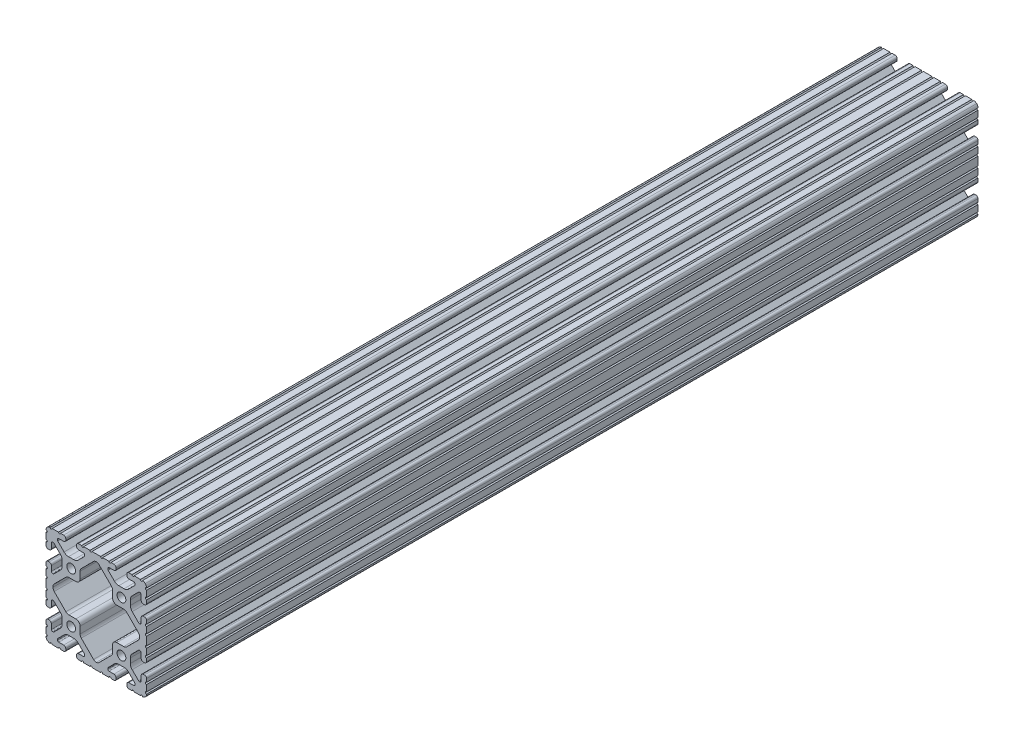
SolidWorks part; units mm, degrees
ref_plane "Front Plane" through (0, 0, 0) normal (0, 0, 1) x (1, 0, 0)
ref_plane "Top Plane" through (0, 0, 0) normal (0, 1, 0) x (1, 0, 0)
ref_plane "Right Plane" through (0, 0, 0) normal (1, 0, 0) x (0, 0, -1)
sketch "Sketch1" plane through (0, 0, 0) normal (0, 0, 1) x (1, 0, 0)
  line L0 (0, 38.1) -> (0, -38.1) construction
  line L1 (-38.1, -38.1) -> (38.1, -38.1) construction
  line L2 (-38.1, -38.1) -> (-38.1, 38.1) construction
  line L3 (-38.1, 38.1) -> (38.1, 38.1) construction
  line L4 (38.1, -38.1) -> (38.1, 38.1) construction
  line L5 (0, 38.1) -> (0, -38.1) construction
  line L6 (-38.1, 0) -> (38.1, 0) construction
  line L7 (-19.05, 19.05) -> (19.05, 19.05) construction
  line L8 (-19.05, 19.05) -> (-19.05, -19.05) construction
  line L9 (-19.05, -19.05) -> (19.05, -19.05) construction
  line L10 (19.05, 19.05) -> (19.05, -19.05) construction
  line L11 (-23.114, 38.1) -> (-23.114, -38.1) construction
  line L12 (-23.114, -38.1) -> (-14.986, 38.1) construction
  line L13 (-14.986, 38.1) -> (-14.986, -38.1) construction
  circle A0 centre (19.05, 19.05) radius 3.3274
  point P0 (0, 0)
  point P9 (0, 0)
  point P12 (-19.05, 0)
  line B0 (-11.3637, -22.8433) -> (-2.0515, -32.1555)
  line B1 (-12.2936, -15.4686) -> (-12.2936, -20.5983)
  line B2 (-20.769, -12.2936) -> (-15.4686, -12.2936)
  line B3 (-31.9021, -2.4756) -> (-23.0141, -11.3637)
  line B4 (-23.0141, 11.3637) -> (-31.9021, 2.4756)
  line B5 (-15.4686, 12.2936) -> (-20.769, 12.2936)
  line B6 (-12.2936, 20.5983) -> (-12.2936, 15.4686)
  line B7 (-2.0515, 32.1555) -> (-11.3637, 22.8433)
  line B8 (11.3637, 22.8433) -> (2.0515, 32.1555)
  line B9 (12.2936, 15.4686) -> (12.2936, 20.5983)
  line B10 (20.769, 12.2936) -> (15.4686, 12.2936)
  line B11 (31.9021, 2.4756) -> (23.0141, 11.3637)
  line B12 (23.0141, -11.3637) -> (31.9021, -2.4756)
  line B13 (15.4686, -12.2936) -> (20.769, -12.2936)
  line B14 (12.2936, -20.5983) -> (12.2936, -15.4686)
  line B15 (2.0515, -32.1555) -> (11.3637, -22.8433)
  line B16 (-4.7773, 38.1) -> (-9.6053, 38.1)
  line B17 (-11.1289, 38.1) -> (-13.4112, 38.1)
  line B18 (-14.986, 36.5252) -> (-14.986, 35.6108)
  line B19 (-13.4112, 34.036) -> (-9.652, 34.036)
  line B20 (-8.763, 33.147) -> (-8.763, 32.4935)
  line B21 (-9.0234, 31.8649) -> (-13.6907, 27.1976)
  line B22 (-17.0493, 25.8064) -> (-21.0507, 25.8064)
  line B23 (-24.4093, 27.1976) -> (-29.1002, 31.8885)
  line B24 (-29.337, 32.7207) -> (-29.337, 33.147)
  line B25 (-28.448, 34.036) -> (-24.6888, 34.036)
  line B26 (-23.114, 35.6108) -> (-23.114, 36.5252)
  line B27 (-24.6888, 38.1) -> (-27.0772, 38.1)
  line B28 (-28.6011, 38.1) -> (-33.4288, 38.1)
  line B29 (-38.1, 33.373) -> (-38.1, 28.5453)
  line B30 (-38.1, 27.0238) -> (-38.1, 24.6302)
  line B31 (-36.5252, 23.0554) -> (-35.6108, 23.0554)
  line B32 (-34.036, 24.6302) -> (-34.036, 28.448)
  line B33 (-33.147, 29.337) -> (-32.6643, 29.337)
  line B34 (-32.0357, 29.0766) -> (-27.1976, 24.2385)
  line B35 (-25.8064, 20.8799) -> (-25.8064, 17.2201)
  line B36 (-27.1976, 13.8615) -> (-31.9489, 9.1101)
  line B37 (-32.7869, 8.763) -> (-33.0603, 8.763)
  line B38 (-34.036, 9.7387) -> (-34.036, 13.4698)
  line B39 (-35.6108, 15.0446) -> (-36.5252, 15.0446)
  line B40 (-38.1, 13.4698) -> (-38.1, 11.075)
  line B41 (-38.1, 9.552) -> (-38.1, 4.7238)
  line B42 (-38.1, 3.2007) -> (-38.1, -3.2007)
  line B43 (-38.1, -4.7238) -> (-38.1, -9.552)
  line B44 (-38.1, -11.075) -> (-38.1, -13.4698)
  line B45 (-36.5252, -15.0446) -> (-35.6108, -15.0446)
  line B46 (-34.036, -13.4698) -> (-34.036, -9.7387)
  line B47 (-33.0603, -8.763) -> (-32.7869, -8.763)
  line B48 (-31.9489, -9.1101) -> (-27.1976, -13.8615)
  line B49 (-25.8064, -17.2201) -> (-25.8064, -20.8799)
  line B50 (-27.1976, -24.2385) -> (-32.0357, -29.0766)
  line B51 (-32.6643, -29.337) -> (-33.147, -29.337)
  line B52 (-34.036, -28.448) -> (-34.036, -24.6302)
  line B53 (-35.6108, -23.0554) -> (-36.5252, -23.0554)
  line B54 (-38.1, -24.6302) -> (-38.1, -27.0238)
  line B55 (-38.1, -28.5453) -> (-38.1, -33.373)
  line B56 (-33.4288, -38.1) -> (-28.6011, -38.1)
  line B57 (-27.0772, -38.1) -> (-24.6888, -38.1)
  line B58 (-23.114, -36.5252) -> (-23.114, -35.6108)
  line B59 (-24.6888, -34.036) -> (-28.448, -34.036)
  line B60 (-29.337, -33.147) -> (-29.337, -32.7207)
  line B61 (-29.1002, -31.8885) -> (-24.4093, -27.1976)
  line B62 (-21.0507, -25.8064) -> (-17.0493, -25.8064)
  line B63 (-13.6907, -27.1976) -> (-9.0234, -31.8649)
  line B64 (-8.763, -32.4935) -> (-8.763, -33.147)
  line B65 (-9.652, -34.036) -> (-13.4112, -34.036)
  line B66 (-14.986, -35.6108) -> (-14.986, -36.5252)
  line B67 (-13.4112, -38.1) -> (-11.1289, -38.1)
  line B68 (-9.6053, -38.1) -> (-4.7773, -38.1)
  line B69 (-3.2537, -38.1) -> (3.2537, -38.1)
  line B70 (4.7773, -38.1) -> (9.6053, -38.1)
  line B71 (11.1289, -38.1) -> (13.4112, -38.1)
  line B72 (14.986, -36.5252) -> (14.986, -35.6108)
  line B73 (13.4112, -34.036) -> (9.652, -34.036)
  line B74 (8.763, -33.147) -> (8.763, -32.4935)
  line B75 (9.0234, -31.8649) -> (13.6907, -27.1976)
  line B76 (17.0493, -25.8064) -> (21.0507, -25.8064)
  line B77 (24.4093, -27.1976) -> (29.1002, -31.8885)
  line B78 (29.337, -32.7207) -> (29.337, -33.147)
  line B79 (28.448, -34.036) -> (24.6888, -34.036)
  line B80 (23.114, -35.6108) -> (23.114, -36.5252)
  line B81 (24.6888, -38.1) -> (27.0772, -38.1)
  line B82 (28.6011, -38.1) -> (33.4288, -38.1)
  line B83 (38.1, -33.373) -> (38.1, -28.5453)
  line B84 (38.1, -27.0238) -> (38.1, -24.6302)
  line B85 (36.5252, -23.0554) -> (35.6108, -23.0554)
  line B86 (34.036, -24.6302) -> (34.036, -28.448)
  line B87 (33.147, -29.337) -> (32.6643, -29.337)
  line B88 (32.0357, -29.0766) -> (27.1976, -24.2385)
  line B89 (25.8064, -20.8799) -> (25.8064, -17.2201)
  line B90 (27.1976, -13.8615) -> (31.9489, -9.1101)
  line B91 (32.7869, -8.763) -> (33.0603, -8.763)
  line B92 (34.036, -9.7387) -> (34.036, -13.4698)
  line B93 (35.6108, -15.0446) -> (36.5252, -15.0446)
  line B94 (38.1, -13.4698) -> (38.1, -11.075)
  line B95 (38.1, -9.552) -> (38.1, -4.7238)
  line B96 (38.1, -3.2007) -> (38.1, 3.2007)
  line B97 (38.1, 4.7238) -> (38.1, 9.552)
  line B98 (38.1, 11.075) -> (38.1, 13.4698)
  line B99 (36.5252, 15.0446) -> (35.6108, 15.0446)
  line B100 (34.036, 13.4698) -> (34.036, 9.7387)
  line B101 (33.0603, 8.763) -> (32.7869, 8.763)
  line B102 (31.9489, 9.1101) -> (27.1976, 13.8615)
  line B103 (25.8064, 17.2201) -> (25.8064, 20.8799)
  line B104 (27.1976, 24.2385) -> (32.0357, 29.0766)
  line B105 (32.6643, 29.337) -> (33.147, 29.337)
  line B106 (34.036, 28.448) -> (34.036, 24.6302)
  line B107 (35.6108, 23.0554) -> (36.5252, 23.0554)
  line B108 (38.1, 24.6302) -> (38.1, 27.0238)
  line B109 (38.1, 28.5453) -> (38.1, 33.373)
  line B110 (33.4288, 38.1) -> (28.6011, 38.1)
  line B111 (27.0772, 38.1) -> (24.6888, 38.1)
  line B112 (23.114, 36.5252) -> (23.114, 35.6108)
  line B113 (24.6888, 34.036) -> (28.448, 34.036)
  line B114 (29.337, 33.147) -> (29.337, 32.7207)
  line B115 (29.1002, 31.8885) -> (24.4093, 27.1976)
  line B116 (21.0507, 25.8064) -> (17.0493, 25.8064)
  line B117 (13.6907, 27.1976) -> (9.0234, 31.8649)
  line B118 (8.763, 32.4935) -> (8.763, 33.147)
  line B119 (9.652, 34.036) -> (13.4112, 34.036)
  line B120 (14.986, 35.6108) -> (14.986, 36.5252)
  line B121 (13.4112, 38.1) -> (11.1289, 38.1)
  line B122 (9.6053, 38.1) -> (4.7773, 38.1)
  line B123 (3.2537, 38.1) -> (-3.2537, 38.1)
  circle B124 centre (-19.05, 19.05) radius 3.3274
  circle B125 centre (-19.05, -19.05) radius 3.3274
  circle B126 centre (19.05, -19.05) radius 3.3274
  circle B127 centre (19.05, 19.05) radius 3.3274
  arc B128 (0, -33.011) -> (2.0515, -32.1555) centre (-0.0139, -30.09) ccw
  arc B129 (-2.0515, -32.1555) -> (0, -33.011) centre (0.0139, -30.09) ccw
  arc B130 (-12.2936, -20.5983) -> (-11.3637, -22.8433) centre (-9.1186, -20.5983) ccw
  arc B131 (-12.2936, -15.4686) -> (-15.4686, -12.2936) centre (-15.4686, -15.4686) ccw
  arc B132 (-23.0141, -11.3637) -> (-20.769, -12.2936) centre (-20.769, -9.1186) ccw
  arc B133 (-32.7287, 0) -> (-31.9021, -2.4756) centre (-29.8367, -0.4102) ccw
  arc B134 (-31.9021, 2.4756) -> (-32.7287, 0) centre (-29.8367, 0.4102) ccw
  arc B135 (-20.769, 12.2936) -> (-23.0141, 11.3637) centre (-20.769, 9.1186) ccw
  arc B136 (-15.4686, 12.2936) -> (-12.2936, 15.4686) centre (-15.4686, 15.4686) ccw
  arc B137 (-11.3637, 22.8433) -> (-12.2936, 20.5983) centre (-9.1186, 20.5983) ccw
  arc B138 (0, 33.011) -> (-2.0515, 32.1555) centre (0.0139, 30.09) ccw
  arc B139 (2.0515, 32.1555) -> (0, 33.011) centre (-0.0139, 30.09) ccw
  arc B140 (12.2936, 20.5983) -> (11.3637, 22.8433) centre (9.1186, 20.5983) ccw
  arc B141 (12.2936, 15.4686) -> (15.4686, 12.2936) centre (15.4686, 15.4686) ccw
  arc B142 (23.0141, 11.3637) -> (20.769, 12.2936) centre (20.769, 9.1186) ccw
  arc B143 (32.7287, 0) -> (31.9021, 2.4756) centre (29.8367, 0.4102) ccw
  arc B144 (31.9021, -2.4756) -> (32.7287, 0) centre (29.8367, -0.4102) ccw
  arc B145 (20.769, -12.2936) -> (23.0141, -11.3637) centre (20.769, -9.1186) ccw
  arc B146 (15.4686, -12.2936) -> (12.2936, -15.4686) centre (15.4686, -15.4686) ccw
  arc B147 (11.3637, -22.8433) -> (12.2936, -20.5983) centre (9.1186, -20.5983) ccw
  arc B148 (-4.7773, 38.1) -> (-3.2537, 38.1) centre (-4.0155, 38.0824) ccw
  arc B149 (-11.1289, 38.1) -> (-9.6053, 38.1) centre (-10.3671, 38.0824) ccw
  arc B150 (-13.4112, 38.1) -> (-14.986, 36.5252) centre (-13.4112, 36.5252) ccw
  arc B151 (-14.986, 35.6108) -> (-13.4112, 34.036) centre (-13.4112, 35.6108) ccw
  arc B152 (-8.763, 33.147) -> (-9.652, 34.036) centre (-9.652, 33.147) ccw
  arc B153 (-9.0234, 31.8649) -> (-8.763, 32.4935) centre (-9.652, 32.4935) ccw
  arc B154 (-17.0493, 25.8064) -> (-13.6907, 27.1976) centre (-17.0493, 30.5562) ccw
  arc B155 (-24.4093, 27.1976) -> (-21.0507, 25.8064) centre (-21.0507, 30.5562) ccw
  arc B156 (-29.337, 32.7207) -> (-29.1002, 31.8885) centre (-28.4716, 32.5172) ccw
  arc B157 (-28.448, 34.036) -> (-29.337, 33.147) centre (-28.448, 33.147) ccw
  arc B158 (-24.6888, 34.036) -> (-23.114, 35.6108) centre (-24.6888, 35.6108) ccw
  arc B159 (-23.114, 36.5252) -> (-24.6888, 38.1) centre (-24.6888, 36.5252) ccw
  arc B160 (-28.6011, 38.1) -> (-27.0772, 38.1) centre (-27.8392, 38.0824) ccw
  arc B161 (-34.9527, 38.1) -> (-33.4288, 38.1) centre (-34.1907, 38.0824) ccw
  arc B162 (-34.9527, 38.1) -> (-37.0861, 37.1826) centre (-34.8521, 34.9266) ccw
  arc B163 (-37.0861, 37.1826) -> (-38.1, 34.8455) centre (-34.925, 34.8566) ccw
  arc B164 (-38.1, 33.373) -> (-38.1, 34.8455) centre (-37.9035, 34.1092) ccw
  arc B165 (-38.1, 27.0238) -> (-38.1, 28.5453) centre (-37.9035, 27.7845) ccw
  arc B166 (-38.1, 24.6302) -> (-36.5252, 23.0554) centre (-36.5252, 24.6302) ccw
  arc B167 (-35.6108, 23.0554) -> (-34.036, 24.6302) centre (-35.6108, 24.6302) ccw
  arc B168 (-33.147, 29.337) -> (-34.036, 28.448) centre (-33.147, 28.448) ccw
  arc B169 (-32.0357, 29.0766) -> (-32.6643, 29.337) centre (-32.6643, 28.448) ccw
  arc B170 (-25.8064, 20.8799) -> (-27.1976, 24.2385) centre (-30.5562, 20.8799) ccw
  arc B171 (-27.1976, 13.8615) -> (-25.8064, 17.2201) centre (-30.5562, 17.2201) ccw
  arc B172 (-32.7869, 8.763) -> (-31.9489, 9.1101) centre (-32.7869, 9.9481) ccw
  arc B173 (-34.036, 9.7387) -> (-33.0603, 8.763) centre (-33.0603, 9.7387) ccw
  arc B174 (-34.036, 13.4698) -> (-35.6108, 15.0446) centre (-35.6108, 13.4698) ccw
  arc B175 (-36.5252, 15.0446) -> (-38.1, 13.4698) centre (-36.5252, 13.4698) ccw
  arc B176 (-38.1, 9.552) -> (-38.1, 11.075) centre (-37.9035, 10.3135) ccw
  arc B177 (-38.1, 3.2007) -> (-38.1, 4.7238) centre (-37.9035, 3.9622) ccw
  arc B178 (-38.1, -4.7238) -> (-38.1, -3.2007) centre (-37.9035, -3.9622) ccw
  arc B179 (-38.1, -11.075) -> (-38.1, -9.552) centre (-37.9035, -10.3135) ccw
  arc B180 (-38.1, -13.4698) -> (-36.5252, -15.0446) centre (-36.5252, -13.4698) ccw
  arc B181 (-35.6108, -15.0446) -> (-34.036, -13.4698) centre (-35.6108, -13.4698) ccw
  arc B182 (-33.0603, -8.763) -> (-34.036, -9.7387) centre (-33.0603, -9.7387) ccw
  arc B183 (-31.9489, -9.1101) -> (-32.7869, -8.763) centre (-32.7869, -9.9481) ccw
  arc B184 (-25.8064, -17.2201) -> (-27.1976, -13.8615) centre (-30.5562, -17.2201) ccw
  arc B185 (-27.1976, -24.2385) -> (-25.8064, -20.8799) centre (-30.5562, -20.8799) ccw
  arc B186 (-32.6643, -29.337) -> (-32.0357, -29.0766) centre (-32.6643, -28.448) ccw
  arc B187 (-34.036, -28.448) -> (-33.147, -29.337) centre (-33.147, -28.448) ccw
  arc B188 (-34.036, -24.6302) -> (-35.6108, -23.0554) centre (-35.6108, -24.6302) ccw
  arc B189 (-36.5252, -23.0554) -> (-38.1, -24.6302) centre (-36.5252, -24.6302) ccw
  arc B190 (-38.1, -28.5453) -> (-38.1, -27.0238) centre (-37.9035, -27.7845) ccw
  arc B191 (-38.1, -34.8455) -> (-38.1, -33.373) centre (-37.9035, -34.1092) ccw
  arc B192 (-38.1, -34.8455) -> (-37.0861, -37.1826) centre (-34.925, -34.8566) ccw
  arc B193 (-37.0861, -37.1826) -> (-34.9527, -38.1) centre (-34.8521, -34.9266) ccw
  arc B194 (-33.4288, -38.1) -> (-34.9527, -38.1) centre (-34.1907, -38.0824) ccw
  arc B195 (-27.0772, -38.1) -> (-28.6011, -38.1) centre (-27.8392, -38.0824) ccw
  arc B196 (-24.6888, -38.1) -> (-23.114, -36.5252) centre (-24.6888, -36.5252) ccw
  arc B197 (-23.114, -35.6108) -> (-24.6888, -34.036) centre (-24.6888, -35.6108) ccw
  arc B198 (-29.337, -33.147) -> (-28.448, -34.036) centre (-28.448, -33.147) ccw
  arc B199 (-29.1002, -31.8885) -> (-29.337, -32.7207) centre (-28.4716, -32.5172) ccw
  arc B200 (-21.0507, -25.8064) -> (-24.4093, -27.1976) centre (-21.0507, -30.5562) ccw
  arc B201 (-13.6907, -27.1976) -> (-17.0493, -25.8064) centre (-17.0493, -30.5562) ccw
  arc B202 (-8.763, -32.4935) -> (-9.0234, -31.8649) centre (-9.652, -32.4935) ccw
  arc B203 (-9.652, -34.036) -> (-8.763, -33.147) centre (-9.652, -33.147) ccw
  arc B204 (-13.4112, -34.036) -> (-14.986, -35.6108) centre (-13.4112, -35.6108) ccw
  arc B205 (-14.986, -36.5252) -> (-13.4112, -38.1) centre (-13.4112, -36.5252) ccw
  arc B206 (-9.6053, -38.1) -> (-11.1289, -38.1) centre (-10.3671, -38.0824) ccw
  arc B207 (-3.2537, -38.1) -> (-4.7773, -38.1) centre (-4.0155, -38.0824) ccw
  arc B208 (4.7773, -38.1) -> (3.2537, -38.1) centre (4.0155, -38.0824) ccw
  arc B209 (11.1289, -38.1) -> (9.6053, -38.1) centre (10.3671, -38.0824) ccw
  arc B210 (13.4112, -38.1) -> (14.986, -36.5252) centre (13.4112, -36.5252) ccw
  arc B211 (14.986, -35.6108) -> (13.4112, -34.036) centre (13.4112, -35.6108) ccw
  arc B212 (8.763, -33.147) -> (9.652, -34.036) centre (9.652, -33.147) ccw
  arc B213 (9.0234, -31.8649) -> (8.763, -32.4935) centre (9.652, -32.4935) ccw
  arc B214 (17.0493, -25.8064) -> (13.6907, -27.1976) centre (17.0493, -30.5562) ccw
  arc B215 (24.4093, -27.1976) -> (21.0507, -25.8064) centre (21.0507, -30.5562) ccw
  arc B216 (29.337, -32.7207) -> (29.1002, -31.8885) centre (28.4716, -32.5172) ccw
  arc B217 (28.448, -34.036) -> (29.337, -33.147) centre (28.448, -33.147) ccw
  arc B218 (24.6888, -34.036) -> (23.114, -35.6108) centre (24.6888, -35.6108) ccw
  arc B219 (23.114, -36.5252) -> (24.6888, -38.1) centre (24.6888, -36.5252) ccw
  arc B220 (28.6011, -38.1) -> (27.0772, -38.1) centre (27.8392, -38.0824) ccw
  arc B221 (34.9527, -38.1) -> (33.4288, -38.1) centre (34.1907, -38.0824) ccw
  arc B222 (34.9527, -38.1) -> (37.0861, -37.1826) centre (34.8521, -34.9266) ccw
  arc B223 (37.0861, -37.1826) -> (38.1, -34.8455) centre (34.925, -34.8566) ccw
  arc B224 (38.1, -33.373) -> (38.1, -34.8455) centre (37.9035, -34.1092) ccw
  arc B225 (38.1, -27.0238) -> (38.1, -28.5453) centre (37.9035, -27.7845) ccw
  arc B226 (38.1, -24.6302) -> (36.5252, -23.0554) centre (36.5252, -24.6302) ccw
  arc B227 (35.6108, -23.0554) -> (34.036, -24.6302) centre (35.6108, -24.6302) ccw
  arc B228 (33.147, -29.337) -> (34.036, -28.448) centre (33.147, -28.448) ccw
  arc B229 (32.0357, -29.0766) -> (32.6643, -29.337) centre (32.6643, -28.448) ccw
  arc B230 (25.8064, -20.8799) -> (27.1976, -24.2385) centre (30.5562, -20.8799) ccw
  arc B231 (27.1976, -13.8615) -> (25.8064, -17.2201) centre (30.5562, -17.2201) ccw
  arc B232 (32.7869, -8.763) -> (31.9489, -9.1101) centre (32.7869, -9.9481) ccw
  arc B233 (34.036, -9.7387) -> (33.0603, -8.763) centre (33.0603, -9.7387) ccw
  arc B234 (34.036, -13.4698) -> (35.6108, -15.0446) centre (35.6108, -13.4698) ccw
  arc B235 (36.5252, -15.0446) -> (38.1, -13.4698) centre (36.5252, -13.4698) ccw
  arc B236 (38.1, -9.552) -> (38.1, -11.075) centre (37.9035, -10.3135) ccw
  arc B237 (38.1, -3.2007) -> (38.1, -4.7238) centre (37.9035, -3.9622) ccw
  arc B238 (38.1, 4.7238) -> (38.1, 3.2007) centre (37.9035, 3.9622) ccw
  arc B239 (38.1, 11.075) -> (38.1, 9.552) centre (37.9035, 10.3135) ccw
  arc B240 (38.1, 13.4698) -> (36.5252, 15.0446) centre (36.5252, 13.4698) ccw
  arc B241 (35.6108, 15.0446) -> (34.036, 13.4698) centre (35.6108, 13.4698) ccw
  arc B242 (33.0603, 8.763) -> (34.036, 9.7387) centre (33.0603, 9.7387) ccw
  arc B243 (31.9489, 9.1101) -> (32.7869, 8.763) centre (32.7869, 9.9481) ccw
  arc B244 (25.8064, 17.2201) -> (27.1976, 13.8615) centre (30.5562, 17.2201) ccw
  arc B245 (27.1976, 24.2385) -> (25.8064, 20.8799) centre (30.5562, 20.8799) ccw
  arc B246 (32.6643, 29.337) -> (32.0357, 29.0766) centre (32.6643, 28.448) ccw
  arc B247 (34.036, 28.448) -> (33.147, 29.337) centre (33.147, 28.448) ccw
  arc B248 (34.036, 24.6302) -> (35.6108, 23.0554) centre (35.6108, 24.6302) ccw
  arc B249 (36.5252, 23.0554) -> (38.1, 24.6302) centre (36.5252, 24.6302) ccw
  arc B250 (38.1, 28.5453) -> (38.1, 27.0238) centre (37.9035, 27.7845) ccw
  arc B251 (38.1, 34.8455) -> (38.1, 33.373) centre (37.9035, 34.1092) ccw
  arc B252 (38.1, 34.8455) -> (37.0861, 37.1826) centre (34.925, 34.8566) ccw
  arc B253 (37.0861, 37.1826) -> (34.9527, 38.1) centre (34.8521, 34.9266) ccw
  arc B254 (33.4288, 38.1) -> (34.9527, 38.1) centre (34.1907, 38.0824) ccw
  arc B255 (27.0772, 38.1) -> (28.6011, 38.1) centre (27.8392, 38.0824) ccw
  arc B256 (24.6888, 38.1) -> (23.114, 36.5252) centre (24.6888, 36.5252) ccw
  arc B257 (23.114, 35.6108) -> (24.6888, 34.036) centre (24.6888, 35.6108) ccw
  arc B258 (29.337, 33.147) -> (28.448, 34.036) centre (28.448, 33.147) ccw
  arc B259 (29.1002, 31.8885) -> (29.337, 32.7207) centre (28.4716, 32.5172) ccw
  arc B260 (21.0507, 25.8064) -> (24.4093, 27.1976) centre (21.0507, 30.5562) ccw
  arc B261 (13.6907, 27.1976) -> (17.0493, 25.8064) centre (17.0493, 30.5562) ccw
  arc B262 (8.763, 32.4935) -> (9.0234, 31.8649) centre (9.652, 32.4935) ccw
  arc B263 (9.652, 34.036) -> (8.763, 33.147) centre (9.652, 33.147) ccw
  arc B264 (13.4112, 34.036) -> (14.986, 35.6108) centre (13.4112, 35.6108) ccw
  arc B265 (14.986, 36.5252) -> (13.4112, 38.1) centre (13.4112, 36.5252) ccw
  arc B266 (9.6053, 38.1) -> (11.1289, 38.1) centre (10.3671, 38.0824) ccw
  arc B267 (3.2537, 38.1) -> (4.7773, 38.1) centre (4.0155, 38.0824) ccw
  dimension "Center Hole Diameter" = 6.6548
  dimension "Rail Width" = 76.2
  dimension "Rail Height" = 76.2
  dimension "T-Slot Width" = 8.128
sketch_block_instance "Block1-1"
sketch_block "Block1"
sketch "Sketch2" plane through (0, 0, 0) normal (1, 0, 0) x (0, 0, -1)
  line L0 (-315, 0) -> (315, 0) construction
  line L1 (-315, 38.1) -> (-315, -38.1) construction
  line L2 (-315, -38.1) -> (315, -38.1) construction
  line L3 (315, -38.1) -> (315, 38.1) construction
  line L4 (-213.4, 0) -> (-213.4, 38.1) construction
  line L5 (-213.4, 38.1) -> (213.4, 38.1) construction
  line L6 (213.4, 38.1) -> (213.4, 0) construction
  point P5 (213.4, 0)
  point P10 (-213.4, 0)
  dimension "D1" = 101.6
  dimension "Length" = 630
  dimension "D2" = 101.6
sketch "Sketch3" plane through (0, 0, 0) normal (0, 0, 1) x (1, 0, 0)
  line L0 (-11.3637, -22.8433) -> (-2.0515, -32.1555) construction
  line L1 (-12.2936, -15.4686) -> (-12.2936, -20.5983) construction
  line L2 (-20.769, -12.2936) -> (-15.4686, -12.2936) construction
  line L3 (-31.9021, -2.4756) -> (-23.0141, -11.3637) construction
  line L4 (-23.0141, 11.3637) -> (-31.9021, 2.4756) construction
  line L5 (-15.4686, 12.2936) -> (-20.769, 12.2936) construction
  line L6 (-12.2936, 20.5983) -> (-12.2936, 15.4686) construction
  line L7 (-2.0515, 32.1555) -> (-11.3637, 22.8433) construction
  line L8 (11.3637, 22.8433) -> (2.0515, 32.1555) construction
  line L9 (12.2936, 15.4686) -> (12.2936, 20.5983) construction
  line L10 (20.769, 12.2936) -> (15.4686, 12.2936) construction
  line L11 (31.9021, 2.4756) -> (23.0141, 11.3637) construction
  line L12 (23.0141, -11.3637) -> (31.9021, -2.4756) construction
  line L13 (15.4686, -12.2936) -> (20.769, -12.2936) construction
  line L14 (12.2936, -20.5983) -> (12.2936, -15.4686) construction
  line L15 (2.0515, -32.1555) -> (11.3637, -22.8433) construction
  line L16 (34.036, 28.448) -> (34.036, 24.6302) construction
  line L17 (35.6108, 23.0554) -> (36.5252, 23.0554) construction
  line L18 (38.1, 24.6302) -> (38.1, 27.0238) construction
  line L19 (38.1, 28.5453) -> (38.1, 33.373) construction
  line L20 (33.4288, 38.1) -> (28.6011, 38.1) construction
  line L21 (27.0772, 38.1) -> (24.6888, 38.1) construction
  line L22 (23.114, 36.5252) -> (23.114, 35.6108) construction
  line L23 (24.6888, 34.036) -> (28.448, 34.036) construction
  line L24 (29.337, 33.147) -> (29.337, 32.7207) construction
  line L25 (29.1002, 31.8885) -> (24.4093, 27.1976) construction
  line L26 (21.0507, 25.8064) -> (17.0493, 25.8064) construction
  line L27 (13.6907, 27.1976) -> (9.0234, 31.8649) construction
  line L28 (8.763, 32.4935) -> (8.763, 33.147) construction
  line L29 (9.652, 34.036) -> (13.4112, 34.036) construction
  line L30 (14.986, 35.6108) -> (14.986, 36.5252) construction
  line L31 (13.4112, 38.1) -> (11.1289, 38.1) construction
  line L32 (9.6053, 38.1) -> (4.7773, 38.1) construction
  line L33 (3.2537, 38.1) -> (-3.2537, 38.1) construction
  line L34 (-4.7773, 38.1) -> (-9.6053, 38.1) construction
  line L35 (-11.1289, 38.1) -> (-13.4112, 38.1) construction
  line L36 (-14.986, 36.5252) -> (-14.986, 35.6108) construction
  line L37 (-13.4112, 34.036) -> (-9.652, 34.036) construction
  line L38 (-8.763, 33.147) -> (-8.763, 32.4935) construction
  line L39 (-9.0234, 31.8649) -> (-13.6907, 27.1976) construction
  line L40 (-17.0493, 25.8064) -> (-21.0507, 25.8064) construction
  line L41 (-24.4093, 27.1976) -> (-29.1002, 31.8885) construction
  line L42 (-29.337, 32.7207) -> (-29.337, 33.147) construction
  line L43 (-28.448, 34.036) -> (-24.6888, 34.036) construction
  line L44 (-23.114, 35.6108) -> (-23.114, 36.5252) construction
  line L45 (-24.6888, 38.1) -> (-27.0772, 38.1) construction
  line L46 (-28.6011, 38.1) -> (-33.4288, 38.1) construction
  line L47 (-38.1, 33.373) -> (-38.1, 28.5453) construction
  line L48 (-38.1, 27.0238) -> (-38.1, 24.6302) construction
  line L49 (-36.5252, 23.0554) -> (-35.6108, 23.0554) construction
  line L50 (-34.036, 24.6302) -> (-34.036, 28.448) construction
  line L51 (-33.147, 29.337) -> (-32.6643, 29.337) construction
  line L52 (-32.0357, 29.0766) -> (-27.1976, 24.2385) construction
  line L53 (-25.8064, 20.8799) -> (-25.8064, 17.2201) construction
  line L54 (-27.1976, 13.8615) -> (-31.9489, 9.1101) construction
  line L55 (-32.7869, 8.763) -> (-33.0603, 8.763) construction
  line L56 (-34.036, 9.7387) -> (-34.036, 13.4698) construction
  line L57 (-35.6108, 15.0446) -> (-36.5252, 15.0446) construction
  line L58 (-38.1, 13.4698) -> (-38.1, 11.075) construction
  line L59 (-38.1, 9.552) -> (-38.1, 4.7238) construction
  line L60 (-38.1, 3.2007) -> (-38.1, -3.2007) construction
  line L61 (-38.1, -4.7238) -> (-38.1, -9.552) construction
  line L62 (-38.1, -11.075) -> (-38.1, -13.4698) construction
  line L63 (-36.5252, -15.0446) -> (-35.6108, -15.0446) construction
  line L64 (-34.036, -13.4698) -> (-34.036, -9.7387) construction
  line L65 (-33.0603, -8.763) -> (-32.7869, -8.763) construction
  line L66 (-31.9489, -9.1101) -> (-27.1976, -13.8615) construction
  line L67 (-25.8064, -17.2201) -> (-25.8064, -20.8799) construction
  line L68 (-27.1976, -24.2385) -> (-32.0357, -29.0766) construction
  line L69 (-32.6643, -29.337) -> (-33.147, -29.337) construction
  line L70 (-34.036, -28.448) -> (-34.036, -24.6302) construction
  line L71 (-35.6108, -23.0554) -> (-36.5252, -23.0554) construction
  line L72 (-38.1, -24.6302) -> (-38.1, -27.0238) construction
  line L73 (-38.1, -28.5453) -> (-38.1, -33.373) construction
  line L74 (-33.4288, -38.1) -> (-28.6011, -38.1) construction
  line L75 (-27.0772, -38.1) -> (-24.6888, -38.1) construction
  line L76 (-23.114, -36.5252) -> (-23.114, -35.6108) construction
  line L77 (-24.6888, -34.036) -> (-28.448, -34.036) construction
  line L78 (-29.337, -33.147) -> (-29.337, -32.7207) construction
  line L79 (-29.1002, -31.8885) -> (-24.4093, -27.1976) construction
  line L80 (-21.0507, -25.8064) -> (-17.0493, -25.8064) construction
  line L81 (-13.6907, -27.1976) -> (-9.0234, -31.8649) construction
  line L82 (-8.763, -32.4935) -> (-8.763, -33.147) construction
  line L83 (-9.652, -34.036) -> (-13.4112, -34.036) construction
  line L84 (-14.986, -35.6108) -> (-14.986, -36.5252) construction
  line L85 (-13.4112, -38.1) -> (-11.1289, -38.1) construction
  line L86 (-9.6053, -38.1) -> (-4.7773, -38.1) construction
  line L87 (-3.2537, -38.1) -> (3.2537, -38.1) construction
  line L88 (4.7773, -38.1) -> (9.6053, -38.1) construction
  line L89 (11.1289, -38.1) -> (13.4112, -38.1) construction
  line L90 (14.986, -36.5252) -> (14.986, -35.6108) construction
  line L91 (13.4112, -34.036) -> (9.652, -34.036) construction
  line L92 (8.763, -33.147) -> (8.763, -32.4935) construction
  line L93 (9.0234, -31.8649) -> (13.6907, -27.1976) construction
  line L94 (17.0493, -25.8064) -> (21.0507, -25.8064) construction
  line L95 (24.4093, -27.1976) -> (29.1002, -31.8885) construction
  line L96 (29.337, -32.7207) -> (29.337, -33.147) construction
  line L97 (28.448, -34.036) -> (24.6888, -34.036) construction
  line L98 (23.114, -35.6108) -> (23.114, -36.5252) construction
  line L99 (24.6888, -38.1) -> (27.0772, -38.1) construction
  line L100 (28.6011, -38.1) -> (33.4288, -38.1) construction
  line L101 (38.1, -33.373) -> (38.1, -28.5453) construction
  line L102 (38.1, -27.0238) -> (38.1, -24.6302) construction
  line L103 (36.5252, -23.0554) -> (35.6108, -23.0554) construction
  line L104 (34.036, -24.6302) -> (34.036, -28.448) construction
  line L105 (33.147, -29.337) -> (32.6643, -29.337) construction
  line L106 (32.0357, -29.0766) -> (27.1976, -24.2385) construction
  line L107 (25.8064, -20.8799) -> (25.8064, -17.2201) construction
  line L108 (27.1976, -13.8615) -> (31.9489, -9.1101) construction
  line L109 (32.7869, -8.763) -> (33.0603, -8.763) construction
  line L110 (34.036, -9.7387) -> (34.036, -13.4698) construction
  line L111 (35.6108, -15.0446) -> (36.5252, -15.0446) construction
  line L112 (38.1, -13.4698) -> (38.1, -11.075) construction
  line L113 (38.1, -9.552) -> (38.1, -4.7238) construction
  line L114 (38.1, -3.2007) -> (38.1, 3.2007) construction
  line L115 (38.1, 4.7238) -> (38.1, 9.552) construction
  line L116 (38.1, 11.075) -> (38.1, 13.4698) construction
  line L117 (36.5252, 15.0446) -> (35.6108, 15.0446) construction
  line L118 (34.036, 13.4698) -> (34.036, 9.7387) construction
  line L119 (33.0603, 8.763) -> (32.7869, 8.763) construction
  line L120 (31.9489, 9.1101) -> (27.1976, 13.8615) construction
  line L121 (25.8064, 17.2201) -> (25.8064, 20.8799) construction
  line L122 (27.1976, 24.2385) -> (32.0357, 29.0766) construction
  line L123 (32.6643, 29.337) -> (33.147, 29.337) construction
  line L124 (-11.3637, -22.8433) -> (-2.0515, -32.1555)
  line L125 (-12.2936, -15.4686) -> (-12.2936, -20.5983)
  line L126 (-20.769, -12.2936) -> (-15.4686, -12.2936)
  line L127 (-31.9021, -2.4756) -> (-23.0141, -11.3637)
  line L128 (-23.0141, 11.3637) -> (-31.9021, 2.4756)
  line L129 (-15.4686, 12.2936) -> (-20.769, 12.2936)
  line L130 (-12.2936, 20.5983) -> (-12.2936, 15.4686)
  line L131 (-2.0515, 32.1555) -> (-11.3637, 22.8433)
  line L132 (11.3637, 22.8433) -> (2.0515, 32.1555)
  line L133 (12.2936, 15.4686) -> (12.2936, 20.5983)
  line L134 (20.769, 12.2936) -> (15.4686, 12.2936)
  line L135 (31.9021, 2.4756) -> (23.0141, 11.3637)
  line L136 (23.0141, -11.3637) -> (31.9021, -2.4756)
  line L137 (15.4686, -12.2936) -> (20.769, -12.2936)
  line L138 (12.2936, -20.5983) -> (12.2936, -15.4686)
  line L139 (2.0515, -32.1555) -> (11.3637, -22.8433)
  line L140 (34.036, 28.448) -> (34.036, 24.6302)
  line L141 (35.6108, 23.0554) -> (36.5252, 23.0554)
  line L142 (38.1, 24.6302) -> (38.1, 27.0238)
  line L143 (38.1, 28.5453) -> (38.1, 33.373)
  line L144 (33.4288, 38.1) -> (28.6011, 38.1)
  line L145 (27.0772, 38.1) -> (24.6888, 38.1)
  line L146 (23.114, 36.5252) -> (23.114, 35.6108)
  line L147 (24.6888, 34.036) -> (28.448, 34.036)
  line L148 (29.337, 33.147) -> (29.337, 32.7207)
  line L149 (29.1002, 31.8885) -> (24.4093, 27.1976)
  line L150 (21.0507, 25.8064) -> (17.0493, 25.8064)
  line L151 (13.6907, 27.1976) -> (9.0234, 31.8649)
  line L152 (8.763, 32.4935) -> (8.763, 33.147)
  line L153 (9.652, 34.036) -> (13.4112, 34.036)
  line L154 (14.986, 35.6108) -> (14.986, 36.5252)
  line L155 (13.4112, 38.1) -> (11.1289, 38.1)
  line L156 (9.6053, 38.1) -> (4.7773, 38.1)
  line L157 (3.2537, 38.1) -> (-3.2537, 38.1)
  line L158 (-4.7773, 38.1) -> (-9.6053, 38.1)
  line L159 (-11.1289, 38.1) -> (-13.4112, 38.1)
  line L160 (-14.986, 36.5252) -> (-14.986, 35.6108)
  line L161 (-13.4112, 34.036) -> (-9.652, 34.036)
  line L162 (-8.763, 33.147) -> (-8.763, 32.4935)
  line L163 (-9.0234, 31.8649) -> (-13.6907, 27.1976)
  line L164 (-17.0493, 25.8064) -> (-21.0507, 25.8064)
  line L165 (-24.4093, 27.1976) -> (-29.1002, 31.8885)
  line L166 (-29.337, 32.7207) -> (-29.337, 33.147)
  line L167 (-28.448, 34.036) -> (-24.6888, 34.036)
  line L168 (-23.114, 35.6108) -> (-23.114, 36.5252)
  line L169 (-24.6888, 38.1) -> (-27.0772, 38.1)
  line L170 (-28.6011, 38.1) -> (-33.4288, 38.1)
  line L171 (-38.1, 33.373) -> (-38.1, 28.5453)
  line L172 (-38.1, 27.0238) -> (-38.1, 24.6302)
  line L173 (-36.5252, 23.0554) -> (-35.6108, 23.0554)
  line L174 (-34.036, 24.6302) -> (-34.036, 28.448)
  line L175 (-33.147, 29.337) -> (-32.6643, 29.337)
  line L176 (-32.0357, 29.0766) -> (-27.1976, 24.2385)
  line L177 (-25.8064, 20.8799) -> (-25.8064, 17.2201)
  line L178 (-27.1976, 13.8615) -> (-31.9489, 9.1101)
  line L179 (-32.7869, 8.763) -> (-33.0603, 8.763)
  line L180 (-34.036, 9.7387) -> (-34.036, 13.4698)
  line L181 (-35.6108, 15.0446) -> (-36.5252, 15.0446)
  line L182 (-38.1, 13.4698) -> (-38.1, 11.075)
  line L183 (-38.1, 9.552) -> (-38.1, 4.7238)
  line L184 (-38.1, 3.2007) -> (-38.1, -3.2007)
  line L185 (-38.1, -4.7238) -> (-38.1, -9.552)
  line L186 (-38.1, -11.075) -> (-38.1, -13.4698)
  line L187 (-36.5252, -15.0446) -> (-35.6108, -15.0446)
  line L188 (-34.036, -13.4698) -> (-34.036, -9.7387)
  line L189 (-33.0603, -8.763) -> (-32.7869, -8.763)
  line L190 (-31.9489, -9.1101) -> (-27.1976, -13.8615)
  line L191 (-25.8064, -17.2201) -> (-25.8064, -20.8799)
  line L192 (-27.1976, -24.2385) -> (-32.0357, -29.0766)
  line L193 (-32.6643, -29.337) -> (-33.147, -29.337)
  line L194 (-34.036, -28.448) -> (-34.036, -24.6302)
  line L195 (-35.6108, -23.0554) -> (-36.5252, -23.0554)
  line L196 (-38.1, -24.6302) -> (-38.1, -27.0238)
  line L197 (-38.1, -28.5453) -> (-38.1, -33.373)
  line L198 (-33.4288, -38.1) -> (-28.6011, -38.1)
  line L199 (-27.0772, -38.1) -> (-24.6888, -38.1)
  line L200 (-23.114, -36.5252) -> (-23.114, -35.6108)
  line L201 (-24.6888, -34.036) -> (-28.448, -34.036)
  line L202 (-29.337, -33.147) -> (-29.337, -32.7207)
  line L203 (-29.1002, -31.8885) -> (-24.4093, -27.1976)
  line L204 (-21.0507, -25.8064) -> (-17.0493, -25.8064)
  line L205 (-13.6907, -27.1976) -> (-9.0234, -31.8649)
  line L206 (-8.763, -32.4935) -> (-8.763, -33.147)
  line L207 (-9.652, -34.036) -> (-13.4112, -34.036)
  line L208 (-14.986, -35.6108) -> (-14.986, -36.5252)
  line L209 (-13.4112, -38.1) -> (-11.1289, -38.1)
  line L210 (-9.6053, -38.1) -> (-4.7773, -38.1)
  line L211 (-3.2537, -38.1) -> (3.2537, -38.1)
  line L212 (4.7773, -38.1) -> (9.6053, -38.1)
  line L213 (11.1289, -38.1) -> (13.4112, -38.1)
  line L214 (14.986, -36.5252) -> (14.986, -35.6108)
  line L215 (13.4112, -34.036) -> (9.652, -34.036)
  line L216 (8.763, -33.147) -> (8.763, -32.4935)
  line L217 (9.0234, -31.8649) -> (13.6907, -27.1976)
  line L218 (17.0493, -25.8064) -> (21.0507, -25.8064)
  line L219 (24.4093, -27.1976) -> (29.1002, -31.8885)
  line L220 (29.337, -32.7207) -> (29.337, -33.147)
  line L221 (28.448, -34.036) -> (24.6888, -34.036)
  line L222 (23.114, -35.6108) -> (23.114, -36.5252)
  line L223 (24.6888, -38.1) -> (27.0772, -38.1)
  line L224 (28.6011, -38.1) -> (33.4288, -38.1)
  line L225 (38.1, -33.373) -> (38.1, -28.5453)
  line L226 (38.1, -27.0238) -> (38.1, -24.6302)
  line L227 (36.5252, -23.0554) -> (35.6108, -23.0554)
  line L228 (34.036, -24.6302) -> (34.036, -28.448)
  line L229 (33.147, -29.337) -> (32.6643, -29.337)
  line L230 (32.0357, -29.0766) -> (27.1976, -24.2385)
  line L231 (25.8064, -20.8799) -> (25.8064, -17.2201)
  line L232 (27.1976, -13.8615) -> (31.9489, -9.1101)
  line L233 (32.7869, -8.763) -> (33.0603, -8.763)
  line L234 (34.036, -9.7387) -> (34.036, -13.4698)
  line L235 (35.6108, -15.0446) -> (36.5252, -15.0446)
  line L236 (38.1, -13.4698) -> (38.1, -11.075)
  line L237 (38.1, -9.552) -> (38.1, -4.7238)
  line L238 (38.1, -3.2007) -> (38.1, 3.2007)
  line L239 (38.1, 4.7238) -> (38.1, 9.552)
  line L240 (38.1, 11.075) -> (38.1, 13.4698)
  line L241 (36.5252, 15.0446) -> (35.6108, 15.0446)
  line L242 (34.036, 13.4698) -> (34.036, 9.7387)
  line L243 (33.0603, 8.763) -> (32.7869, 8.763)
  line L244 (31.9489, 9.1101) -> (27.1976, 13.8615)
  line L245 (25.8064, 17.2201) -> (25.8064, 20.8799)
  line L246 (27.1976, 24.2385) -> (32.0357, 29.0766)
  line L247 (32.6643, 29.337) -> (33.147, 29.337)
  arc A0 (-2.0515, -32.1555) -> (0, -33.011) centre (0.0139, -30.09) ccw construction
  circle A1 centre (19.05, 19.05) radius 3.3274
  circle A2 centre (19.05, 19.05) radius 3.3274
  arc A3 (-12.2936, -20.5983) -> (-11.3637, -22.8433) centre (-9.1186, -20.5983) ccw construction
  arc A4 (-12.2936, -15.4686) -> (-15.4686, -12.2936) centre (-15.4686, -15.4686) ccw construction
  arc A5 (-23.0141, -11.3637) -> (-20.769, -12.2936) centre (-20.769, -9.1186) ccw construction
  arc A6 (-32.7287, 0) -> (-31.9021, -2.4756) centre (-29.8367, -0.4102) ccw construction
  arc A7 (-31.9021, 2.4756) -> (-32.7287, 0) centre (-29.8367, 0.4102) ccw construction
  arc A8 (-20.769, 12.2936) -> (-23.0141, 11.3637) centre (-20.769, 9.1186) ccw construction
  arc A9 (-15.4686, 12.2936) -> (-12.2936, 15.4686) centre (-15.4686, 15.4686) ccw construction
  arc A10 (-11.3637, 22.8433) -> (-12.2936, 20.5983) centre (-9.1186, 20.5983) ccw construction
  arc A11 (0, 33.011) -> (-2.0515, 32.1555) centre (0.0139, 30.09) ccw construction
  arc A12 (2.0515, 32.1555) -> (0, 33.011) centre (-0.0139, 30.09) ccw construction
  arc A13 (12.2936, 20.5983) -> (11.3637, 22.8433) centre (9.1186, 20.5983) ccw construction
  arc A14 (12.2936, 15.4686) -> (15.4686, 12.2936) centre (15.4686, 15.4686) ccw construction
  arc A15 (23.0141, 11.3637) -> (20.769, 12.2936) centre (20.769, 9.1186) ccw construction
  arc A16 (32.7287, 0) -> (31.9021, 2.4756) centre (29.8367, 0.4102) ccw construction
  arc A17 (31.9021, -2.4756) -> (32.7287, 0) centre (29.8367, -0.4102) ccw construction
  arc A18 (20.769, -12.2936) -> (23.0141, -11.3637) centre (20.769, -9.1186) ccw construction
  arc A19 (15.4686, -12.2936) -> (12.2936, -15.4686) centre (15.4686, -15.4686) ccw construction
  arc A20 (11.3637, -22.8433) -> (12.2936, -20.5983) centre (9.1186, -20.5983) ccw construction
  arc A21 (0, -33.011) -> (2.0515, -32.1555) centre (-0.0139, -30.09) ccw construction
  circle A22 centre (-19.05, 19.05) radius 3.3274 construction
  circle A23 centre (19.05, -19.05) radius 3.3274 construction
  circle A24 centre (-19.05, -19.05) radius 3.3274 construction
  circle A25 centre (19.05, 19.05) radius 3.3274 construction
  arc A26 (34.036, 24.6302) -> (35.6108, 23.0554) centre (35.6108, 24.6302) ccw construction
  arc A27 (36.5252, 23.0554) -> (38.1, 24.6302) centre (36.5252, 24.6302) ccw construction
  arc A28 (38.1, 28.5453) -> (38.1, 27.0238) centre (37.9035, 27.7845) ccw construction
  arc A29 (38.1, 34.8455) -> (38.1, 33.373) centre (37.9035, 34.1092) ccw construction
  arc A30 (38.1, 34.8455) -> (37.0861, 37.1826) centre (34.925, 34.8566) ccw construction
  arc A31 (37.0861, 37.1826) -> (34.9527, 38.1) centre (34.8521, 34.9266) ccw construction
  arc A32 (33.4288, 38.1) -> (34.9527, 38.1) centre (34.1907, 38.0824) ccw construction
  arc A33 (27.0772, 38.1) -> (28.6011, 38.1) centre (27.8392, 38.0824) ccw construction
  arc A34 (24.6888, 38.1) -> (23.114, 36.5252) centre (24.6888, 36.5252) ccw construction
  arc A35 (23.114, 35.6108) -> (24.6888, 34.036) centre (24.6888, 35.6108) ccw construction
  arc A36 (29.337, 33.147) -> (28.448, 34.036) centre (28.448, 33.147) ccw construction
  arc A37 (29.1002, 31.8885) -> (29.337, 32.7207) centre (28.4716, 32.5172) ccw construction
  arc A38 (21.0507, 25.8064) -> (24.4093, 27.1976) centre (21.0507, 30.5562) ccw construction
  arc A39 (13.6907, 27.1976) -> (17.0493, 25.8064) centre (17.0493, 30.5562) ccw construction
  arc A40 (8.763, 32.4935) -> (9.0234, 31.8649) centre (9.652, 32.4935) ccw construction
  arc A41 (9.652, 34.036) -> (8.763, 33.147) centre (9.652, 33.147) ccw construction
  arc A42 (13.4112, 34.036) -> (14.986, 35.6108) centre (13.4112, 35.6108) ccw construction
  arc A43 (14.986, 36.5252) -> (13.4112, 38.1) centre (13.4112, 36.5252) ccw construction
  arc A44 (9.6053, 38.1) -> (11.1289, 38.1) centre (10.3671, 38.0824) ccw construction
  arc A45 (3.2537, 38.1) -> (4.7773, 38.1) centre (4.0155, 38.0824) ccw construction
  arc A46 (-4.7773, 38.1) -> (-3.2537, 38.1) centre (-4.0155, 38.0824) ccw construction
  arc A47 (-11.1289, 38.1) -> (-9.6053, 38.1) centre (-10.3671, 38.0824) ccw construction
  arc A48 (-13.4112, 38.1) -> (-14.986, 36.5252) centre (-13.4112, 36.5252) ccw construction
  arc A49 (-14.986, 35.6108) -> (-13.4112, 34.036) centre (-13.4112, 35.6108) ccw construction
  arc A50 (-8.763, 33.147) -> (-9.652, 34.036) centre (-9.652, 33.147) ccw construction
  arc A51 (-9.0234, 31.8649) -> (-8.763, 32.4935) centre (-9.652, 32.4935) ccw construction
  arc A52 (-17.0493, 25.8064) -> (-13.6907, 27.1976) centre (-17.0493, 30.5562) ccw construction
  arc A53 (-24.4093, 27.1976) -> (-21.0507, 25.8064) centre (-21.0507, 30.5562) ccw construction
  arc A54 (-29.337, 32.7207) -> (-29.1002, 31.8885) centre (-28.4716, 32.5172) ccw construction
  arc A55 (-28.448, 34.036) -> (-29.337, 33.147) centre (-28.448, 33.147) ccw construction
  arc A56 (-24.6888, 34.036) -> (-23.114, 35.6108) centre (-24.6888, 35.6108) ccw construction
  arc A57 (-23.114, 36.5252) -> (-24.6888, 38.1) centre (-24.6888, 36.5252) ccw construction
  arc A58 (-28.6011, 38.1) -> (-27.0772, 38.1) centre (-27.8392, 38.0824) ccw construction
  arc A59 (-34.9527, 38.1) -> (-33.4288, 38.1) centre (-34.1907, 38.0824) ccw construction
  arc A60 (-34.9527, 38.1) -> (-37.0861, 37.1826) centre (-34.8521, 34.9266) ccw construction
  arc A61 (-37.0861, 37.1826) -> (-38.1, 34.8455) centre (-34.925, 34.8566) ccw construction
  arc A62 (-38.1, 33.373) -> (-38.1, 34.8455) centre (-37.9035, 34.1092) ccw construction
  arc A63 (-38.1, 27.0238) -> (-38.1, 28.5453) centre (-37.9035, 27.7845) ccw construction
  arc A64 (-38.1, 24.6302) -> (-36.5252, 23.0554) centre (-36.5252, 24.6302) ccw construction
  arc A65 (-35.6108, 23.0554) -> (-34.036, 24.6302) centre (-35.6108, 24.6302) ccw construction
  arc A66 (-33.147, 29.337) -> (-34.036, 28.448) centre (-33.147, 28.448) ccw construction
  arc A67 (-32.0357, 29.0766) -> (-32.6643, 29.337) centre (-32.6643, 28.448) ccw construction
  arc A68 (-25.8064, 20.8799) -> (-27.1976, 24.2385) centre (-30.5562, 20.8799) ccw construction
  arc A69 (-27.1976, 13.8615) -> (-25.8064, 17.2201) centre (-30.5562, 17.2201) ccw construction
  arc A70 (-32.7869, 8.763) -> (-31.9489, 9.1101) centre (-32.7869, 9.9481) ccw construction
  arc A71 (-34.036, 9.7387) -> (-33.0603, 8.763) centre (-33.0603, 9.7387) ccw construction
  arc A72 (-34.036, 13.4698) -> (-35.6108, 15.0446) centre (-35.6108, 13.4698) ccw construction
  arc A73 (-36.5252, 15.0446) -> (-38.1, 13.4698) centre (-36.5252, 13.4698) ccw construction
  arc A74 (-38.1, 9.552) -> (-38.1, 11.075) centre (-37.9035, 10.3135) ccw construction
  arc A75 (-38.1, 3.2007) -> (-38.1, 4.7238) centre (-37.9035, 3.9622) ccw construction
  arc A76 (-38.1, -4.7238) -> (-38.1, -3.2007) centre (-37.9035, -3.9622) ccw construction
  arc A77 (-38.1, -11.075) -> (-38.1, -9.552) centre (-37.9035, -10.3135) ccw construction
  arc A78 (-38.1, -13.4698) -> (-36.5252, -15.0446) centre (-36.5252, -13.4698) ccw construction
  arc A79 (-35.6108, -15.0446) -> (-34.036, -13.4698) centre (-35.6108, -13.4698) ccw construction
  arc A80 (-33.0603, -8.763) -> (-34.036, -9.7387) centre (-33.0603, -9.7387) ccw construction
  arc A81 (-31.9489, -9.1101) -> (-32.7869, -8.763) centre (-32.7869, -9.9481) ccw construction
  arc A82 (-25.8064, -17.2201) -> (-27.1976, -13.8615) centre (-30.5562, -17.2201) ccw construction
  arc A83 (-27.1976, -24.2385) -> (-25.8064, -20.8799) centre (-30.5562, -20.8799) ccw construction
  arc A84 (-32.6643, -29.337) -> (-32.0357, -29.0766) centre (-32.6643, -28.448) ccw construction
  arc A85 (-34.036, -28.448) -> (-33.147, -29.337) centre (-33.147, -28.448) ccw construction
  arc A86 (-34.036, -24.6302) -> (-35.6108, -23.0554) centre (-35.6108, -24.6302) ccw construction
  arc A87 (-36.5252, -23.0554) -> (-38.1, -24.6302) centre (-36.5252, -24.6302) ccw construction
  arc A88 (-38.1, -28.5453) -> (-38.1, -27.0238) centre (-37.9035, -27.7845) ccw construction
  arc A89 (-38.1, -34.8455) -> (-38.1, -33.373) centre (-37.9035, -34.1092) ccw construction
  arc A90 (-38.1, -34.8455) -> (-37.0861, -37.1826) centre (-34.925, -34.8566) ccw construction
  arc A91 (-37.0861, -37.1826) -> (-34.9527, -38.1) centre (-34.8521, -34.9266) ccw construction
  arc A92 (-33.4288, -38.1) -> (-34.9527, -38.1) centre (-34.1907, -38.0824) ccw construction
  arc A93 (-27.0772, -38.1) -> (-28.6011, -38.1) centre (-27.8392, -38.0824) ccw construction
  arc A94 (-24.6888, -38.1) -> (-23.114, -36.5252) centre (-24.6888, -36.5252) ccw construction
  arc A95 (-23.114, -35.6108) -> (-24.6888, -34.036) centre (-24.6888, -35.6108) ccw construction
  arc A96 (-29.337, -33.147) -> (-28.448, -34.036) centre (-28.448, -33.147) ccw construction
  arc A97 (-29.1002, -31.8885) -> (-29.337, -32.7207) centre (-28.4716, -32.5172) ccw construction
  arc A98 (-21.0507, -25.8064) -> (-24.4093, -27.1976) centre (-21.0507, -30.5562) ccw construction
  arc A99 (-13.6907, -27.1976) -> (-17.0493, -25.8064) centre (-17.0493, -30.5562) ccw construction
  arc A100 (-8.763, -32.4935) -> (-9.0234, -31.8649) centre (-9.652, -32.4935) ccw construction
  arc A101 (-9.652, -34.036) -> (-8.763, -33.147) centre (-9.652, -33.147) ccw construction
  arc A102 (-13.4112, -34.036) -> (-14.986, -35.6108) centre (-13.4112, -35.6108) ccw construction
  arc A103 (-14.986, -36.5252) -> (-13.4112, -38.1) centre (-13.4112, -36.5252) ccw construction
  arc A104 (-9.6053, -38.1) -> (-11.1289, -38.1) centre (-10.3671, -38.0824) ccw construction
  arc A105 (-3.2537, -38.1) -> (-4.7773, -38.1) centre (-4.0155, -38.0824) ccw construction
  arc A106 (4.7773, -38.1) -> (3.2537, -38.1) centre (4.0155, -38.0824) ccw construction
  arc A107 (11.1289, -38.1) -> (9.6053, -38.1) centre (10.3671, -38.0824) ccw construction
  arc A108 (13.4112, -38.1) -> (14.986, -36.5252) centre (13.4112, -36.5252) ccw construction
  arc A109 (14.986, -35.6108) -> (13.4112, -34.036) centre (13.4112, -35.6108) ccw construction
  arc A110 (8.763, -33.147) -> (9.652, -34.036) centre (9.652, -33.147) ccw construction
  arc A111 (9.0234, -31.8649) -> (8.763, -32.4935) centre (9.652, -32.4935) ccw construction
  arc A112 (17.0493, -25.8064) -> (13.6907, -27.1976) centre (17.0493, -30.5562) ccw construction
  arc A113 (24.4093, -27.1976) -> (21.0507, -25.8064) centre (21.0507, -30.5562) ccw construction
  arc A114 (29.337, -32.7207) -> (29.1002, -31.8885) centre (28.4716, -32.5172) ccw construction
  arc A115 (28.448, -34.036) -> (29.337, -33.147) centre (28.448, -33.147) ccw construction
  arc A116 (24.6888, -34.036) -> (23.114, -35.6108) centre (24.6888, -35.6108) ccw construction
  arc A117 (23.114, -36.5252) -> (24.6888, -38.1) centre (24.6888, -36.5252) ccw construction
  arc A118 (28.6011, -38.1) -> (27.0772, -38.1) centre (27.8392, -38.0824) ccw construction
  arc A119 (34.9527, -38.1) -> (33.4288, -38.1) centre (34.1907, -38.0824) ccw construction
  arc A120 (34.9527, -38.1) -> (37.0861, -37.1826) centre (34.8521, -34.9266) ccw construction
  arc A121 (37.0861, -37.1826) -> (38.1, -34.8455) centre (34.925, -34.8566) ccw construction
  arc A122 (38.1, -33.373) -> (38.1, -34.8455) centre (37.9035, -34.1092) ccw construction
  arc A123 (38.1, -27.0238) -> (38.1, -28.5453) centre (37.9035, -27.7845) ccw construction
  arc A124 (38.1, -24.6302) -> (36.5252, -23.0554) centre (36.5252, -24.6302) ccw construction
  arc A125 (35.6108, -23.0554) -> (34.036, -24.6302) centre (35.6108, -24.6302) ccw construction
  arc A126 (33.147, -29.337) -> (34.036, -28.448) centre (33.147, -28.448) ccw construction
  arc A127 (32.0357, -29.0766) -> (32.6643, -29.337) centre (32.6643, -28.448) ccw construction
  arc A128 (25.8064, -20.8799) -> (27.1976, -24.2385) centre (30.5562, -20.8799) ccw construction
  arc A129 (27.1976, -13.8615) -> (25.8064, -17.2201) centre (30.5562, -17.2201) ccw construction
  arc A130 (32.7869, -8.763) -> (31.9489, -9.1101) centre (32.7869, -9.9481) ccw construction
  arc A131 (34.036, -9.7387) -> (33.0603, -8.763) centre (33.0603, -9.7387) ccw construction
  arc A132 (34.036, -13.4698) -> (35.6108, -15.0446) centre (35.6108, -13.4698) ccw construction
  arc A133 (36.5252, -15.0446) -> (38.1, -13.4698) centre (36.5252, -13.4698) ccw construction
  arc A134 (38.1, -9.552) -> (38.1, -11.075) centre (37.9035, -10.3135) ccw construction
  arc A135 (38.1, -3.2007) -> (38.1, -4.7238) centre (37.9035, -3.9622) ccw construction
  arc A136 (38.1, 4.7238) -> (38.1, 3.2007) centre (37.9035, 3.9622) ccw construction
  arc A137 (38.1, 11.075) -> (38.1, 9.552) centre (37.9035, 10.3135) ccw construction
  arc A138 (38.1, 13.4698) -> (36.5252, 15.0446) centre (36.5252, 13.4698) ccw construction
  arc A139 (35.6108, 15.0446) -> (34.036, 13.4698) centre (35.6108, 13.4698) ccw construction
  arc A140 (33.0603, 8.763) -> (34.036, 9.7387) centre (33.0603, 9.7387) ccw construction
  arc A141 (31.9489, 9.1101) -> (32.7869, 8.763) centre (32.7869, 9.9481) ccw construction
  arc A142 (25.8064, 17.2201) -> (27.1976, 13.8615) centre (30.5562, 17.2201) ccw construction
  arc A143 (27.1976, 24.2385) -> (25.8064, 20.8799) centre (30.5562, 20.8799) ccw construction
  arc A144 (32.6643, 29.337) -> (32.0357, 29.0766) centre (32.6643, 28.448) ccw construction
  arc A145 (34.036, 28.448) -> (33.147, 29.337) centre (33.147, 28.448) ccw construction
  arc A146 (-2.0515, -32.1555) -> (0, -33.011) centre (0.0139, -30.09) ccw
  arc A147 (-12.2936, -20.5983) -> (-11.3637, -22.8433) centre (-9.1186, -20.5983) ccw
  arc A148 (-12.2936, -15.4686) -> (-15.4686, -12.2936) centre (-15.4686, -15.4686) ccw
  arc A149 (-23.0141, -11.3637) -> (-20.769, -12.2936) centre (-20.769, -9.1186) ccw
  arc A150 (-32.7287, 0) -> (-31.9021, -2.4756) centre (-29.8367, -0.4102) ccw
  arc A151 (-31.9021, 2.4756) -> (-32.7287, 0) centre (-29.8367, 0.4102) ccw
  arc A152 (-20.769, 12.2936) -> (-23.0141, 11.3637) centre (-20.769, 9.1186) ccw
  arc A153 (-15.4686, 12.2936) -> (-12.2936, 15.4686) centre (-15.4686, 15.4686) ccw
  arc A154 (-11.3637, 22.8433) -> (-12.2936, 20.5983) centre (-9.1186, 20.5983) ccw
  arc A155 (0, 33.011) -> (-2.0515, 32.1555) centre (0.0139, 30.09) ccw
  arc A156 (2.0515, 32.1555) -> (0, 33.011) centre (-0.0139, 30.09) ccw
  arc A157 (12.2936, 20.5983) -> (11.3637, 22.8433) centre (9.1186, 20.5983) ccw
  arc A158 (12.2936, 15.4686) -> (15.4686, 12.2936) centre (15.4686, 15.4686) ccw
  arc A159 (23.0141, 11.3637) -> (20.769, 12.2936) centre (20.769, 9.1186) ccw
  arc A160 (32.7287, 0) -> (31.9021, 2.4756) centre (29.8367, 0.4102) ccw
  arc A161 (31.9021, -2.4756) -> (32.7287, 0) centre (29.8367, -0.4102) ccw
  arc A162 (20.769, -12.2936) -> (23.0141, -11.3637) centre (20.769, -9.1186) ccw
  arc A163 (15.4686, -12.2936) -> (12.2936, -15.4686) centre (15.4686, -15.4686) ccw
  arc A164 (11.3637, -22.8433) -> (12.2936, -20.5983) centre (9.1186, -20.5983) ccw
  arc A165 (0, -33.011) -> (2.0515, -32.1555) centre (-0.0139, -30.09) ccw
  circle A166 centre (-19.05, 19.05) radius 3.3274
  circle A167 centre (19.05, -19.05) radius 3.3274
  circle A168 centre (-19.05, -19.05) radius 3.3274
  circle A169 centre (19.05, 19.05) radius 3.3274
  arc A170 (34.036, 24.6302) -> (35.6108, 23.0554) centre (35.6108, 24.6302) ccw
  arc A171 (36.5252, 23.0554) -> (38.1, 24.6302) centre (36.5252, 24.6302) ccw
  arc A172 (38.1, 28.5453) -> (38.1, 27.0238) centre (37.9035, 27.7845) ccw
  arc A173 (38.1, 34.8455) -> (38.1, 33.373) centre (37.9035, 34.1092) ccw
  arc A174 (38.1, 34.8455) -> (37.0861, 37.1826) centre (34.925, 34.8566) ccw
  arc A175 (37.0861, 37.1826) -> (34.9527, 38.1) centre (34.8521, 34.9266) ccw
  arc A176 (33.4288, 38.1) -> (34.9527, 38.1) centre (34.1907, 38.0824) ccw
  arc A177 (27.0772, 38.1) -> (28.6011, 38.1) centre (27.8392, 38.0824) ccw
  arc A178 (24.6888, 38.1) -> (23.114, 36.5252) centre (24.6888, 36.5252) ccw
  arc A179 (23.114, 35.6108) -> (24.6888, 34.036) centre (24.6888, 35.6108) ccw
  arc A180 (29.337, 33.147) -> (28.448, 34.036) centre (28.448, 33.147) ccw
  arc A181 (29.1002, 31.8885) -> (29.337, 32.7207) centre (28.4716, 32.5172) ccw
  arc A182 (21.0507, 25.8064) -> (24.4093, 27.1976) centre (21.0507, 30.5562) ccw
  arc A183 (13.6907, 27.1976) -> (17.0493, 25.8064) centre (17.0493, 30.5562) ccw
  arc A184 (8.763, 32.4935) -> (9.0234, 31.8649) centre (9.652, 32.4935) ccw
  arc A185 (9.652, 34.036) -> (8.763, 33.147) centre (9.652, 33.147) ccw
  arc A186 (13.4112, 34.036) -> (14.986, 35.6108) centre (13.4112, 35.6108) ccw
  arc A187 (14.986, 36.5252) -> (13.4112, 38.1) centre (13.4112, 36.5252) ccw
  arc A188 (9.6053, 38.1) -> (11.1289, 38.1) centre (10.3671, 38.0824) ccw
  arc A189 (3.2537, 38.1) -> (4.7773, 38.1) centre (4.0155, 38.0824) ccw
  arc A190 (-4.7773, 38.1) -> (-3.2537, 38.1) centre (-4.0155, 38.0824) ccw
  arc A191 (-11.1289, 38.1) -> (-9.6053, 38.1) centre (-10.3671, 38.0824) ccw
  arc A192 (-13.4112, 38.1) -> (-14.986, 36.5252) centre (-13.4112, 36.5252) ccw
  arc A193 (-14.986, 35.6108) -> (-13.4112, 34.036) centre (-13.4112, 35.6108) ccw
  arc A194 (-8.763, 33.147) -> (-9.652, 34.036) centre (-9.652, 33.147) ccw
  arc A195 (-9.0234, 31.8649) -> (-8.763, 32.4935) centre (-9.652, 32.4935) ccw
  arc A196 (-17.0493, 25.8064) -> (-13.6907, 27.1976) centre (-17.0493, 30.5562) ccw
  arc A197 (-24.4093, 27.1976) -> (-21.0507, 25.8064) centre (-21.0507, 30.5562) ccw
  arc A198 (-29.337, 32.7207) -> (-29.1002, 31.8885) centre (-28.4716, 32.5172) ccw
  arc A199 (-28.448, 34.036) -> (-29.337, 33.147) centre (-28.448, 33.147) ccw
  arc A200 (-24.6888, 34.036) -> (-23.114, 35.6108) centre (-24.6888, 35.6108) ccw
  arc A201 (-23.114, 36.5252) -> (-24.6888, 38.1) centre (-24.6888, 36.5252) ccw
  arc A202 (-28.6011, 38.1) -> (-27.0772, 38.1) centre (-27.8392, 38.0824) ccw
  arc A203 (-34.9527, 38.1) -> (-33.4288, 38.1) centre (-34.1907, 38.0824) ccw
  arc A204 (-34.9527, 38.1) -> (-37.0861, 37.1826) centre (-34.8521, 34.9266) ccw
  arc A205 (-37.0861, 37.1826) -> (-38.1, 34.8455) centre (-34.925, 34.8566) ccw
  arc A206 (-38.1, 33.373) -> (-38.1, 34.8455) centre (-37.9035, 34.1092) ccw
  arc A207 (-38.1, 27.0238) -> (-38.1, 28.5453) centre (-37.9035, 27.7845) ccw
  arc A208 (-38.1, 24.6302) -> (-36.5252, 23.0554) centre (-36.5252, 24.6302) ccw
  arc A209 (-35.6108, 23.0554) -> (-34.036, 24.6302) centre (-35.6108, 24.6302) ccw
  arc A210 (-33.147, 29.337) -> (-34.036, 28.448) centre (-33.147, 28.448) ccw
  arc A211 (-32.0357, 29.0766) -> (-32.6643, 29.337) centre (-32.6643, 28.448) ccw
  arc A212 (-25.8064, 20.8799) -> (-27.1976, 24.2385) centre (-30.5562, 20.8799) ccw
  arc A213 (-27.1976, 13.8615) -> (-25.8064, 17.2201) centre (-30.5562, 17.2201) ccw
  arc A214 (-32.7869, 8.763) -> (-31.9489, 9.1101) centre (-32.7869, 9.9481) ccw
  arc A215 (-34.036, 9.7387) -> (-33.0603, 8.763) centre (-33.0603, 9.7387) ccw
  arc A216 (-34.036, 13.4698) -> (-35.6108, 15.0446) centre (-35.6108, 13.4698) ccw
  arc A217 (-36.5252, 15.0446) -> (-38.1, 13.4698) centre (-36.5252, 13.4698) ccw
  arc A218 (-38.1, 9.552) -> (-38.1, 11.075) centre (-37.9035, 10.3135) ccw
  arc A219 (-38.1, 3.2007) -> (-38.1, 4.7238) centre (-37.9035, 3.9622) ccw
  arc A220 (-38.1, -4.7238) -> (-38.1, -3.2007) centre (-37.9035, -3.9622) ccw
  arc A221 (-38.1, -11.075) -> (-38.1, -9.552) centre (-37.9035, -10.3135) ccw
  arc A222 (-38.1, -13.4698) -> (-36.5252, -15.0446) centre (-36.5252, -13.4698) ccw
  arc A223 (-35.6108, -15.0446) -> (-34.036, -13.4698) centre (-35.6108, -13.4698) ccw
  arc A224 (-33.0603, -8.763) -> (-34.036, -9.7387) centre (-33.0603, -9.7387) ccw
  arc A225 (-31.9489, -9.1101) -> (-32.7869, -8.763) centre (-32.7869, -9.9481) ccw
  arc A226 (-25.8064, -17.2201) -> (-27.1976, -13.8615) centre (-30.5562, -17.2201) ccw
  arc A227 (-27.1976, -24.2385) -> (-25.8064, -20.8799) centre (-30.5562, -20.8799) ccw
  arc A228 (-32.6643, -29.337) -> (-32.0357, -29.0766) centre (-32.6643, -28.448) ccw
  arc A229 (-34.036, -28.448) -> (-33.147, -29.337) centre (-33.147, -28.448) ccw
  arc A230 (-34.036, -24.6302) -> (-35.6108, -23.0554) centre (-35.6108, -24.6302) ccw
  arc A231 (-36.5252, -23.0554) -> (-38.1, -24.6302) centre (-36.5252, -24.6302) ccw
  arc A232 (-38.1, -28.5453) -> (-38.1, -27.0238) centre (-37.9035, -27.7845) ccw
  arc A233 (-38.1, -34.8455) -> (-38.1, -33.373) centre (-37.9035, -34.1092) ccw
  arc A234 (-38.1, -34.8455) -> (-37.0861, -37.1826) centre (-34.925, -34.8566) ccw
  arc A235 (-37.0861, -37.1826) -> (-34.9527, -38.1) centre (-34.8521, -34.9266) ccw
  arc A236 (-33.4288, -38.1) -> (-34.9527, -38.1) centre (-34.1907, -38.0824) ccw
  arc A237 (-27.0772, -38.1) -> (-28.6011, -38.1) centre (-27.8392, -38.0824) ccw
  arc A238 (-24.6888, -38.1) -> (-23.114, -36.5252) centre (-24.6888, -36.5252) ccw
  arc A239 (-23.114, -35.6108) -> (-24.6888, -34.036) centre (-24.6888, -35.6108) ccw
  arc A240 (-29.337, -33.147) -> (-28.448, -34.036) centre (-28.448, -33.147) ccw
  arc A241 (-29.1002, -31.8885) -> (-29.337, -32.7207) centre (-28.4716, -32.5172) ccw
  arc A242 (-21.0507, -25.8064) -> (-24.4093, -27.1976) centre (-21.0507, -30.5562) ccw
  arc A243 (-13.6907, -27.1976) -> (-17.0493, -25.8064) centre (-17.0493, -30.5562) ccw
  arc A244 (-8.763, -32.4935) -> (-9.0234, -31.8649) centre (-9.652, -32.4935) ccw
  arc A245 (-9.652, -34.036) -> (-8.763, -33.147) centre (-9.652, -33.147) ccw
  arc A246 (-13.4112, -34.036) -> (-14.986, -35.6108) centre (-13.4112, -35.6108) ccw
  arc A247 (-14.986, -36.5252) -> (-13.4112, -38.1) centre (-13.4112, -36.5252) ccw
  arc A248 (-9.6053, -38.1) -> (-11.1289, -38.1) centre (-10.3671, -38.0824) ccw
  arc A249 (-3.2537, -38.1) -> (-4.7773, -38.1) centre (-4.0155, -38.0824) ccw
  arc A250 (4.7773, -38.1) -> (3.2537, -38.1) centre (4.0155, -38.0824) ccw
  arc A251 (11.1289, -38.1) -> (9.6053, -38.1) centre (10.3671, -38.0824) ccw
  arc A252 (13.4112, -38.1) -> (14.986, -36.5252) centre (13.4112, -36.5252) ccw
  arc A253 (14.986, -35.6108) -> (13.4112, -34.036) centre (13.4112, -35.6108) ccw
  arc A254 (8.763, -33.147) -> (9.652, -34.036) centre (9.652, -33.147) ccw
  arc A255 (9.0234, -31.8649) -> (8.763, -32.4935) centre (9.652, -32.4935) ccw
  arc A256 (17.0493, -25.8064) -> (13.6907, -27.1976) centre (17.0493, -30.5562) ccw
  arc A257 (24.4093, -27.1976) -> (21.0507, -25.8064) centre (21.0507, -30.5562) ccw
  arc A258 (29.337, -32.7207) -> (29.1002, -31.8885) centre (28.4716, -32.5172) ccw
  arc A259 (28.448, -34.036) -> (29.337, -33.147) centre (28.448, -33.147) ccw
  arc A260 (24.6888, -34.036) -> (23.114, -35.6108) centre (24.6888, -35.6108) ccw
  arc A261 (23.114, -36.5252) -> (24.6888, -38.1) centre (24.6888, -36.5252) ccw
  arc A262 (28.6011, -38.1) -> (27.0772, -38.1) centre (27.8392, -38.0824) ccw
  arc A263 (34.9527, -38.1) -> (33.4288, -38.1) centre (34.1907, -38.0824) ccw
  arc A264 (34.9527, -38.1) -> (37.0861, -37.1826) centre (34.8521, -34.9266) ccw
  arc A265 (37.0861, -37.1826) -> (38.1, -34.8455) centre (34.925, -34.8566) ccw
  arc A266 (38.1, -33.373) -> (38.1, -34.8455) centre (37.9035, -34.1092) ccw
  arc A267 (38.1, -27.0238) -> (38.1, -28.5453) centre (37.9035, -27.7845) ccw
  arc A268 (38.1, -24.6302) -> (36.5252, -23.0554) centre (36.5252, -24.6302) ccw
  arc A269 (35.6108, -23.0554) -> (34.036, -24.6302) centre (35.6108, -24.6302) ccw
  arc A270 (33.147, -29.337) -> (34.036, -28.448) centre (33.147, -28.448) ccw
  arc A271 (32.0357, -29.0766) -> (32.6643, -29.337) centre (32.6643, -28.448) ccw
  arc A272 (25.8064, -20.8799) -> (27.1976, -24.2385) centre (30.5562, -20.8799) ccw
  arc A273 (27.1976, -13.8615) -> (25.8064, -17.2201) centre (30.5562, -17.2201) ccw
  arc A274 (32.7869, -8.763) -> (31.9489, -9.1101) centre (32.7869, -9.9481) ccw
  arc A275 (34.036, -9.7387) -> (33.0603, -8.763) centre (33.0603, -9.7387) ccw
  arc A276 (34.036, -13.4698) -> (35.6108, -15.0446) centre (35.6108, -13.4698) ccw
  arc A277 (36.5252, -15.0446) -> (38.1, -13.4698) centre (36.5252, -13.4698) ccw
  arc A278 (38.1, -9.552) -> (38.1, -11.075) centre (37.9035, -10.3135) ccw
  arc A279 (38.1, -3.2007) -> (38.1, -4.7238) centre (37.9035, -3.9622) ccw
  arc A280 (38.1, 4.7238) -> (38.1, 3.2007) centre (37.9035, 3.9622) ccw
  arc A281 (38.1, 11.075) -> (38.1, 9.552) centre (37.9035, 10.3135) ccw
  arc A282 (38.1, 13.4698) -> (36.5252, 15.0446) centre (36.5252, 13.4698) ccw
  arc A283 (35.6108, 15.0446) -> (34.036, 13.4698) centre (35.6108, 13.4698) ccw
  arc A284 (33.0603, 8.763) -> (34.036, 9.7387) centre (33.0603, 9.7387) ccw
  arc A285 (31.9489, 9.1101) -> (32.7869, 8.763) centre (32.7869, 9.9481) ccw
  arc A286 (25.8064, 17.2201) -> (27.1976, 13.8615) centre (30.5562, 17.2201) ccw
  arc A287 (27.1976, 24.2385) -> (25.8064, 20.8799) centre (30.5562, 20.8799) ccw
  arc A288 (32.6643, 29.337) -> (32.0357, 29.0766) centre (32.6643, 28.448) ccw
  arc A289 (34.036, 28.448) -> (33.147, 29.337) centre (33.147, 28.448) ccw
  dimension "D1" = 0
extrude "Boss-Extrude1" add sketch "Sketch3" along normal up to vertex (315 mm away) and the other way up to vertex (315 mm away) contours A289 L140 A170 L141 A171 L142 A172 L143 A173 A174 A175 A176 L144 A177 L145 A178 L146 A179 L147 A180 L148 A181 L149 A182 L150 A183 L151 A184 L152 A185 L153 A186 L154 A187 L155 A188 L156 A189 L157 A190 L158 A191 L159 A192 L160 A193 L161 A194 L162 A195 L163 up to point (0, 0, 315) other way up to point (0, 0, -315)
